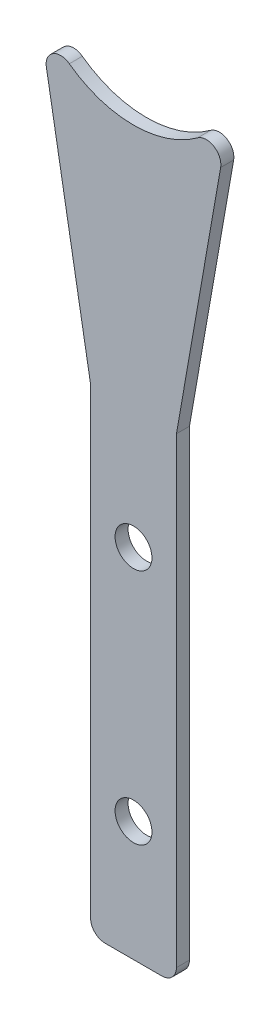
SolidWorks part; units mm, degrees
material "Custom Plastic"
ref_plane "X-Y Datum" through (0, 0, 0) normal (0, 0, 1) x (1, 0, 0)
ref_plane "X-Z Datum" through (0, 0, 0) normal (0, 1, 0) x (1, 0, 0)
ref_plane "Y-Z Datum" through (0, 0, 0) normal (1, 0, 0) x (0, 0, -1)
sketch "Sketch1" plane through (0, 0, 0) normal (0, 0, 1) x (1, 0, 0)
  line L0 (2.16, -14.0069) -> (2.16, -28.6179)
  line L2 (-3.0789, -28.6179) -> (-3.0789, 29.5681)
  line L5 (-3.0789, -28.6179) -> (7.3985, -28.6179)
  line L6 (-3.0789, 29.5681) -> (2.16, 29.5681)
  line L7 (7.3985, -28.6179) -> (7.3985, 29.5681)
  line L8 (-3.0789, 29.5681) -> (-9.5806, 66.7194)
  line L9 (7.3985, 29.5681) -> (13.8967, 66.7194)
  circle A5 centre (2.158, 72.7781) radius 13.21
  circle A6 centre (2.16, 14.9571) radius 2
  circle A7 centre (2.16, -14.0069) radius 2
  point P0 (0, 0)
  dimension "D1" = 26.42
  dimension "D2" = 4
  dimension "D3" = 4
  dimension "D4" = 28.964
  dimension "D5" = 14.611
extrude "Boss-Extrude1" add sketch "Sketch1" along normal blind 1.5875
fillet "Fillet2" radius 1.778 4 edges at (7.3985, -28.6179, 0.7937) (-3.0789, -28.6179, 0.7937) (-9.5806, 66.7194, 0.7937) (13.8967, 66.7194, 0.7937)
hole_wizard "M4 Clearance Hole2" positions "Sketch4" profile "Sketch5" hole size "M4" standard "ANSI Metric" end condition through all
sketch "Sketch4" plane through (0, 0, 1.5875) normal (0, 0, 1) x (1, 0, 0)
  point P0 (2.16, 14.9571)
  point P3 (2.16, -14.0069)
sketch "Sketch5" plane through (2.16, 14.9571, 1.5875) normal (1, 0, 0) x (0, -1, 0)
  line L0 (0, 0) -> (0, 1.5875)
  line L1 (0, 1.5875) -> (2.25, 1.5875)
  line L2 (2.25, 1.5875) -> (2.25, 0)
  line L5 (2.25, 0) -> (0, 0)
  line L11 (0, -6.35) -> (0, 107.95) construction
  dimension "Thru Hole Dia." = 4.5
  dimension "Thru Hole Depth" = 1.5875
